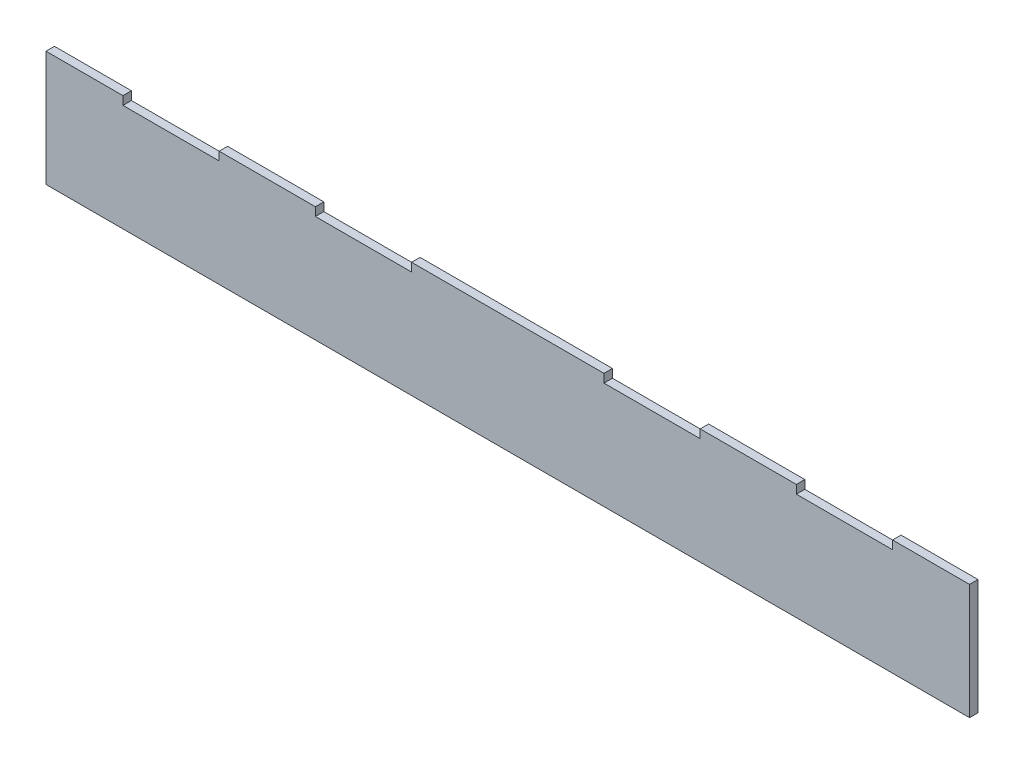
SolidWorks part; units mm, degrees
ref_plane "Front Plane" through (0, 0, 0) normal (0, 0, 1) x (1, 0, 0)
ref_plane "Top Plane" through (0, 0, 0) normal (0, 1, 0) x (1, 0, 0)
ref_plane "Right Plane" through (0, 0, 0) normal (1, 0, 0) x (0, 0, -1)
sketch "Sketch1" plane through (0, 0, 0) normal (0, 0, 1) x (1, 0, 0)
  line L0 (-496.9718, -40.2902) -> (-496.9718, 35.9098) construction
  line L1 (-801.7718, 35.9098) -> (-750.9718, 35.9098)
  line L2 (-801.7718, 35.9098) -> (-801.7718, -40.2902)
  line L3 (-801.7718, -40.2902) -> (-192.1718, -40.2902)
  line L4 (-192.1718, 35.9098) -> (-192.1718, -40.2902)
  line L5 (-687.4718, 35.9098) -> (-623.9718, 35.9098)
  line L6 (-560.4718, 35.9098) -> (-433.4718, 35.9098)
  line L7 (-750.9718, 35.9098) -> (-750.9718, 30.3218)
  line L8 (-750.9718, 30.3218) -> (-687.4718, 30.3218)
  line L9 (-687.4718, 35.9098) -> (-687.4718, 30.3218)
  line L10 (-433.4718, 35.9098) -> (-433.4718, 30.3218)
  line L11 (-623.9718, 35.9098) -> (-623.9718, 30.3218)
  line L12 (-623.9718, 30.3218) -> (-560.4718, 30.3218)
  line L13 (-560.4718, 35.9098) -> (-560.4718, 30.3218)
  line L14 (-369.9718, 30.3218) -> (-433.4718, 30.3218)
  line L15 (-369.9718, 35.9098) -> (-369.9718, 30.3218)
  line L16 (-306.4718, 35.9098) -> (-369.9718, 35.9098)
  line L17 (-306.4718, 35.9098) -> (-306.4718, 30.3218)
  line L18 (-242.9718, 30.3218) -> (-306.4718, 30.3218)
  line L19 (-242.9718, 35.9098) -> (-242.9718, 30.3218)
  line L20 (-192.1718, 35.9098) -> (-242.9718, 35.9098)
  point P14 (-560.4718, 33.1158)
  dimension "D1" = 609.6
  dimension "D2" = 76.2
  dimension "D3" = 63.5
  dimension "D4" = 63.5
  dimension "D5" = 63.5
  dimension "D6" = 5.588
  dimension "D7" = 5.588
  dimension "D8" = 5.588
extrude "Boss-Extrude1" add sketch "Sketch1" along normal blind 5.588
equation "\"width\"= 9in"
equation "\"Height\"= 18in"
equation "\"thick\"= 0.22"
equation "\"D1@Boss-Extrude1\"=\"thick\""
equation "\"D6@Sketch1\"=\"thick\""
equation "\"D7@Sketch1\"=\"thick\""
equation "\"D8@Sketch1\"=\"thick\""
